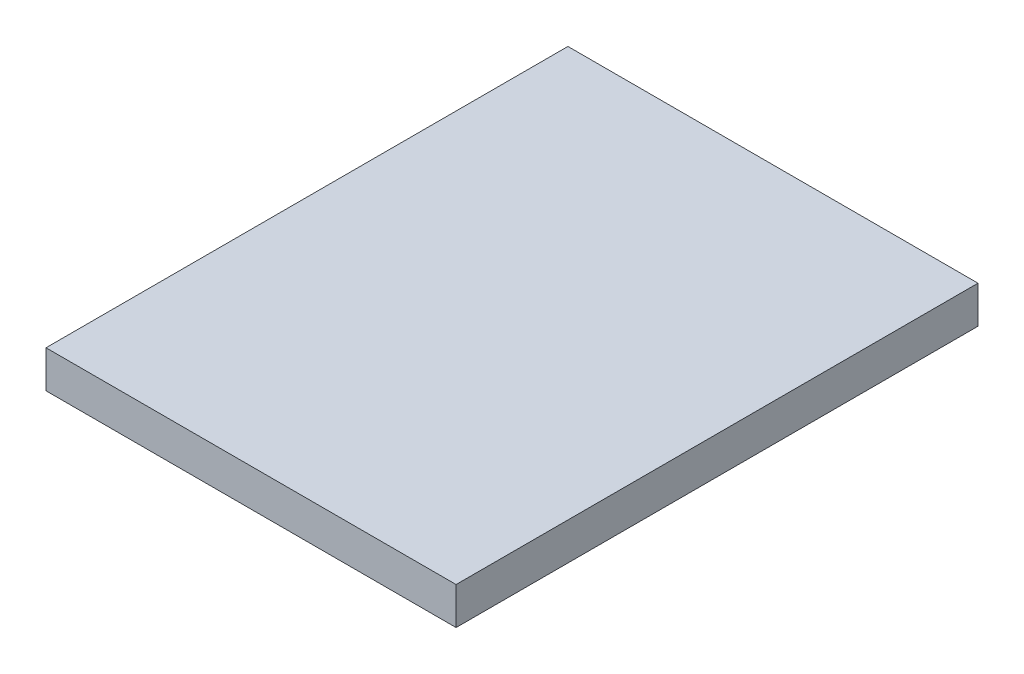
SolidWorks part; units mm, degrees
ref_plane "Front Plane" through (0, 0, 0) normal (0, 0, 1) x (1, 0, 0)
ref_plane "Top Plane" through (0, 0, 0) normal (0, 1, 0) x (1, 0, 0)
ref_plane "Right Plane" through (0, 0, 0) normal (1, 0, 0) x (0, 0, -1)
sketch "Sketch1" plane through (0, 0, 0) normal (0, 1, 0) x (1, 0, 0)
  line L1 (-55, -70) -> (55, -70)
  line L2 (-55, -70) -> (-55, 70)
  line L3 (-55, 70) -> (55, 70)
  line L4 (55, -70) -> (55, 70)
  line L5 (-55, -70) -> (55, 70) construction
  line L6 (-55, 70) -> (55, -70) construction
  point P0 (0, 0)
  dimension "D1" = 140
  dimension "D2" = 110
extrude "Boss-Extrude1" add sketch "Sketch1" along normal blind 10
